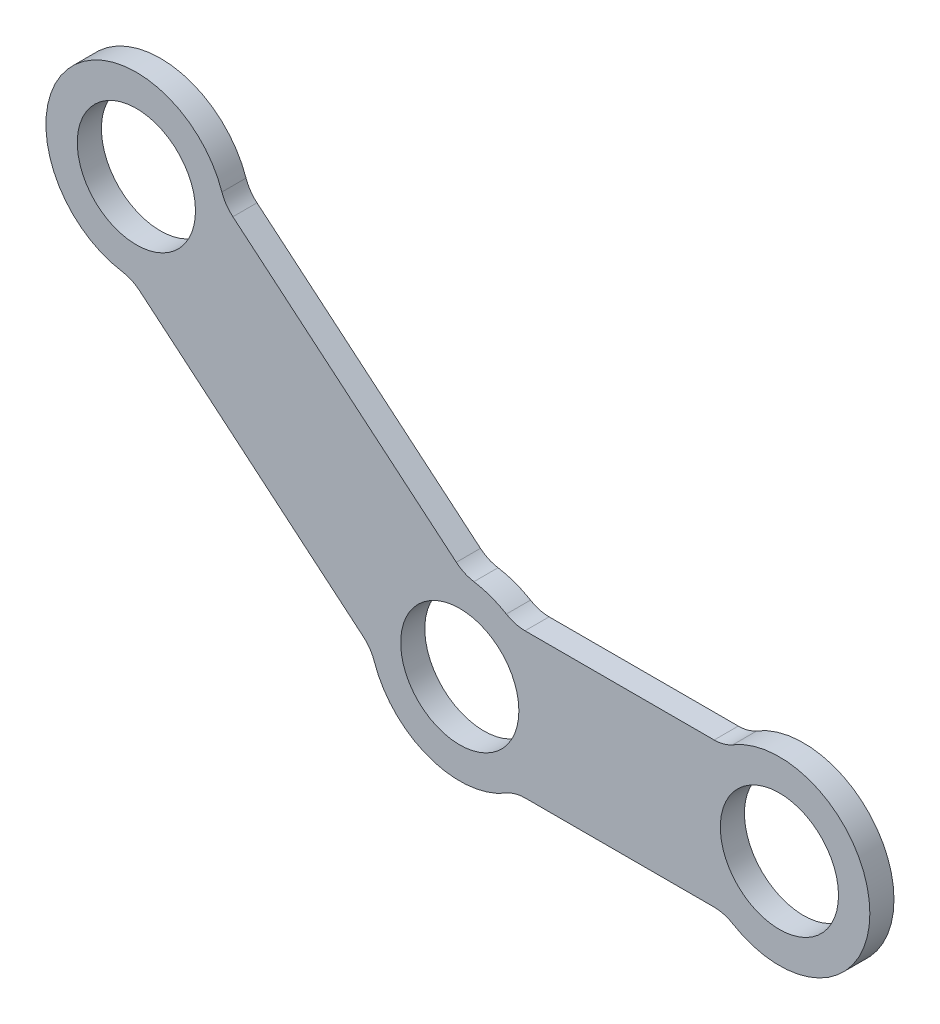
SolidWorks part; units mm, degrees
ref_plane "Front Plane" through (0, 0, 0) normal (0, 0, 1) x (1, 0, 0)
ref_plane "Top Plane" through (0, 0, 0) normal (0, 1, 0) x (1, 0, 0)
ref_plane "Right Plane" through (0, 0, 0) normal (1, 0, 0) x (0, 0, -1)
sketch "Sketch1" plane through (0, 0, 0) normal (0, 0, 1) x (1, 0, 0)
  line L0 (4.5, 0) -> (21.3038, 0) construction
  line L1 (4.5, 6) -> (22, 6)
  line L2 (4.5, 6) -> (4.5, -6)
  line L3 (4.5, -6) -> (22, -6)
  line L4 (26.5, 0) -> (21.6, 0) construction
  line L5 (0, 0) -> (4.9, 0) construction
  line L6 (0, 0) -> (12.1963, 33.5092) construction
  line L7 (0, 0) -> (-3.7536, 3.1497) construction
  line L8 (-3.4472, 2.8925) -> (-16.3197, 13.6938) construction
  line L9 (0.4095, 7.4888) -> (-19.5076, 24.2013)
  line L10 (-7.3039, -1.7037) -> (-20.7097, 9.5451)
  line L11 (0.4095, 7.4888) -> (-7.3039, -1.7037)
  line L12 (0.4095, 7.4888) -> (-12.9963, 18.7376)
  line L13 (-7.3039, -1.7037) -> (-27.2211, 15.0088)
  circle A0 centre (0, 0) radius 4.9
  circle A1 centre (0, 0) radius 7.5
  circle A2 centre (26.5, 0) radius 4.9
  circle A3 centre (26.5, 0) radius 7.5
  circle A4 centre (-26.8116, 22.4976) radius 7.5
  circle A5 centre (-26.8116, 22.4976) radius 4.9
  dimension "D1" = 9.8
  dimension "D2" = 9.8
  dimension "D3" = 15
  dimension "D4" = 15
  dimension "D8" = 35
  dimension "D9" = 9.8
  dimension "D10" = 15
  dimension "D5" = 26.5
  dimension "D6" = 12
  dimension "D7" = 70
extrude "Boss-Extrude1" add sketch "Sketch1" along normal blind 2 contours A4 A5 | L12 A4 L10 A1 | A3 L1 A1 L3 | A3 A2 | L11 A1 | L2 A1 | L11 A1 L2 A0 | L2 A1 L11 A0
fillet "Fillet1" radius 3 8 edges at (-7.3039, -1.7037, 1) (-27.2211, 15.0088, 1) (4.5, -6, 1) (22, -6, 1) (22, 6, 1) (4.5, 6, 1) (0.4095, 7.4888, 1) (-19.5076, 24.2013, 1)
